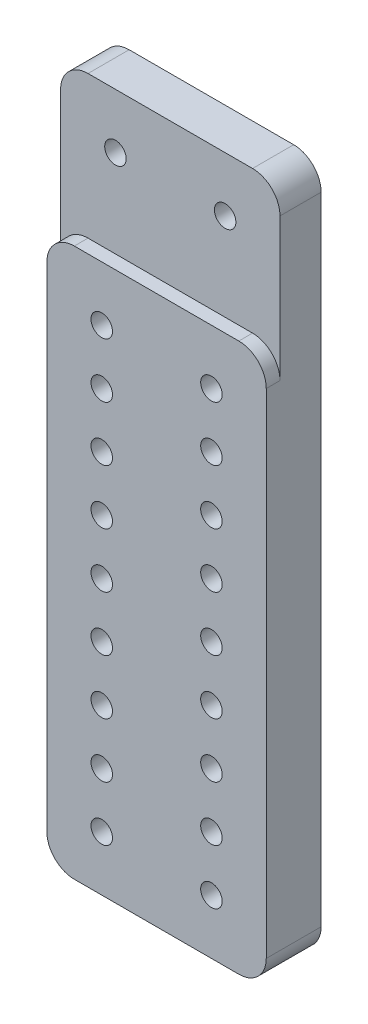
SolidWorks part; units mm, degrees
material "PET"
ref_plane "Front Plane" through (0, 0, 0) normal (0, 0, 1) x (1, 0, 0)
ref_plane "Top Plane" through (0, 0, 0) normal (0, 1, 0) x (1, 0, 0)
ref_plane "Right Plane" through (0, 0, 0) normal (1, 0, 0) x (0, 0, -1)
sketch "Sketch2" plane through (0, 0, 0) normal (0, 0, 1) x (1, 0, 0)
  line L1 (0, 0) -> (50.8, 0)
  line L2 (0, 0) -> (0, 160.02)
  line L3 (0, 160.02) -> (50.8, 160.02)
  line L4 (50.8, 0) -> (50.8, 160.02)
  dimension "D1" = 50.8
  dimension "D2" = 160.02
extrude "Boss-Extrude1" add sketch "Sketch2" against normal blind 12.7
sketch "Sketch3" plane through (0, 0, 0) normal (0, 0, 1) x (1, 0, 0)
  line L0 (50.8, 160.02) -> (0, 160.02) construction
  line L1 (0, 160.02) -> (0, 0) construction
  circle A0 centre (12.7, 147.32) radius 2.4892
  circle A17 centre (38.1, 147.32) radius 2.4892
  circle A24 centre (12.7, 114.3) radius 2.4892
  circle A25 centre (12.7, 101.6) radius 2.4892
  circle A26 centre (12.7, 88.9) radius 2.4892
  circle A27 centre (12.7, 76.2) radius 2.4892
  circle A28 centre (12.7, 63.5) radius 2.4892
  circle A29 centre (38.1, 101.6) radius 2.4892
  circle A30 centre (38.1, 88.9) radius 2.4892
  circle A31 centre (38.1, 76.2) radius 2.4892
  circle A32 centre (38.1, 63.5) radius 2.4892
  circle A33 centre (38.1, 114.3) radius 2.4892
  circle A34 centre (12.7, 50.8) radius 2.4892
  circle A35 centre (12.7, 38.1) radius 2.4892
  circle A36 centre (12.7, 25.4) radius 2.4892
  circle A37 centre (12.7, 12.7) radius 2.4892
  circle A38 centre (38.1, 50.8) radius 2.4892
  circle A39 centre (38.1, 38.1) radius 2.4892
  circle A40 centre (38.1, 25.4) radius 2.4892
  circle A41 centre (38.1, 12.7) radius 2.4892
  dimension "D1" = 4.9784
  dimension "D6" = 4.9784
  dimension "D2" = 12.7
  dimension "D3" = 12.7
  dimension "D7" = 12.7
  dimension "D8" = 33.02
  dimension "D4" = 1
  dimension "D5" = 2
  dimension "D9" = 9
  dimension "D10" = 2
extrude "Cut-Extrude1" cut sketch "Sketch3" against normal through all
fillet "Fillet1" radius 6.35 4 edges at (0, 0, -6.35) (50.8, 0, -6.35) (50.8, 160.02, -6.35) (0, 160.02, -6.35)
sketch "Sketch4" plane through (0, 0, 0) normal (-1, 0, 0) x (0, 0, 1)
  line L1 (-3.175, 160.02) -> (0, 160.02)
  line L2 (-3.175, 160.02) -> (-3.175, 127)
  line L3 (-3.175, 127) -> (0, 127)
  line L4 (0, 160.02) -> (0, 127)
  line L5 (0, 153.67) -> (0, 6.35) construction
  line L6 (-12.7, 160.02) -> (0, 160.02) construction
  point P8 (0, 0)
  dimension "D1" = 33.02
  dimension "D2" = 3.175
extrude "Cut-Extrude2" cut sketch "Sketch4" against normal through all
fillet "Fillet3" radius 6.35 2 edges at (50.8, 127, -1.5875) (0, 127, -1.5875)
